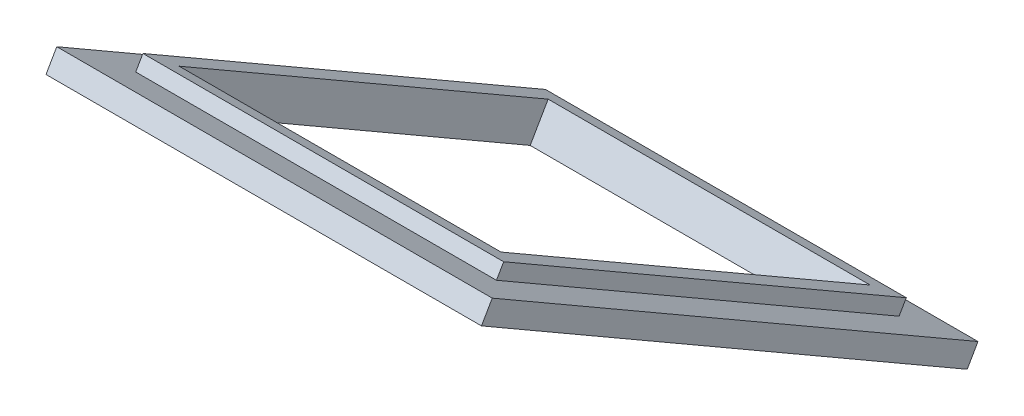
SolidWorks part; units mm, degrees
ref_plane "Front Plane" through (0, 0, 0) normal (0, 0, 1) x (1, 0, 0)
ref_plane "Top Plane" through (0, 0, 0) normal (0, 1, 0) x (1, 0, 0)
ref_plane "Right Plane" through (0, 0, 0) normal (1, 0, 0) x (0, 0, -1)
sketch "Sketch1" plane through (0, -784.0347, -1198.7114) normal (0, 0.866, -0.5) x (1, 0, 0)
  line L4 (-38.1078, -1476.2164) -> (22.4922, -1476.2164)
  line L6 (22.4922, -1476.2164) -> (22.4922, -1398.1585)
  line L7 (22.4922, -1398.1585) -> (-38.1078, -1398.1585)
  line L20 (-38.1078, -1398.1585) -> (-38.1078, -1476.2164)
  line L21 (14.5922, -1466.8338) -> (14.5922, -1407.5338)
  line L22 (-30.2078, -1466.8338) -> (14.5922, -1466.8338)
  line L23 (-30.2078, -1407.5338) -> (-30.2078, -1466.8338)
  line L24 (14.5922, -1407.5338) -> (-30.2078, -1407.5338)
  line L25 (14.5922, -1466.8338) -> (14.5922, -1407.5338)
  line L26 (-30.2078, -1466.8338) -> (14.5922, -1466.8338)
  line L27 (-30.2078, -1407.5338) -> (-30.2078, -1466.8338)
  line L29 (14.5922, -1407.5338) -> (-30.2078, -1407.5338)
  line L31 (22.5922, -1476.3164) -> (22.5922, -1398.0585)
  line L32 (-38.2078, -1476.3164) -> (22.5922, -1476.3164)
  line L33 (-38.2078, -1398.0585) -> (-38.2078, -1476.3164)
  line L34 (22.5922, -1398.0585) -> (-38.2078, -1398.0585)
  line L35 (22.5922, -1476.3164) -> (22.5922, -1398.0585) construction
  line L36 (-38.2078, -1476.3164) -> (22.5922, -1476.3164) construction
  line L37 (-38.2078, -1398.0585) -> (-38.2078, -1476.3164) construction
  line L38 (22.5922, -1398.0585) -> (-38.2078, -1398.0585) construction
  dimension "D1" = 0
  dimension "D2" = 0
  dimension "D3" = 0.1
extrude "Boss-Extrude1" add sketch "Sketch1" against normal up to vertex (3 mm away)
sketch "Sketch2" plane through (0, -68.9688, 39.8191) normal (0, 0.866, -0.5) x (1, 0, 0)
  line L4 (14.5922, -36.7019) -> (14.5922, 22.5981)
  line L5 (-30.2078, -36.7019) -> (14.5922, -36.7019)
  line L6 (-30.2078, 22.5981) -> (-30.2078, -36.7019)
  line L7 (14.5922, 22.5981) -> (-30.2078, 22.5981)
  line L8 (-33.2078, -39.7019) -> (17.5922, -39.7019) construction
  line L9 (-32.9078, 25.2981) -> (17.2922, 25.2981)
  line L10 (-32.9078, 25.2981) -> (-32.9078, -39.4019)
  line L11 (-32.9078, -39.4019) -> (17.2922, -39.4019)
  line L12 (17.2922, 25.2981) -> (17.2922, -39.4019)
  line L13 (17.5922, -39.7019) -> (17.5922, 25.5981) construction
  line L14 (-33.2078, 25.5981) -> (-33.2078, -39.7019) construction
  line L15 (17.5922, 25.5981) -> (-33.2078, 25.5981) construction
  dimension "D1" = 0.3
  dimension "D2" = 0.3
  dimension "D3" = 0.3
  dimension "D4" = 0.3
  dimension "D5" = 14.5922
  dimension "D6" = 30.2078
  dimension "D7" = 22.5981
  dimension "D8" = 36.7019
extrude "Boss-Extrude2" add sketch "Sketch2" along normal up to surface (2 mm away)
